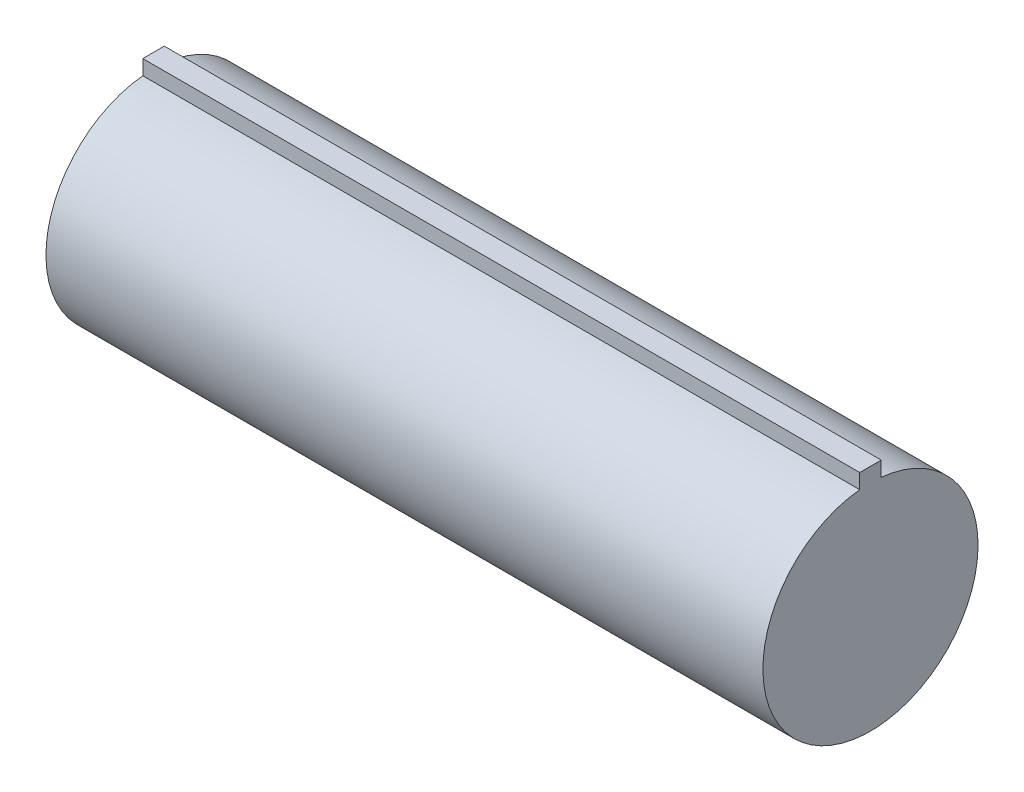
SolidWorks part; units mm, degrees
ref_plane "前视基准面" through (0, 0, 0) normal (0, 0, 1) x (1, 0, 0)
ref_plane "上视基准面" through (0, 0, 0) normal (0, 1, 0) x (1, 0, 0)
ref_plane "右视基准面" through (0, 0, 0) normal (1, 0, 0) x (0, 0, -1)
other "Configuration Table"
sketch "草图1" plane through (0, 0, 0) normal (1, 0, 0) x (0, 0, -1)
  line L1 (-1.5, 0) -> (1.5, 0)
  line L2 (-1.5, 0) -> (-1.5, 17)
  line L3 (-1.5, 17) -> (1.5, 17)
  line L4 (1.5, 0) -> (1.5, 17)
  circle A0 centre (0, 0) radius 15
  point P7 (0, 0)
  dimension "D1" = 30
  dimension "D2" = 3
  dimension "D3" = 17
extrude "凸台-拉伸1" add sketch "草图1" along normal blind 100 from offset 0 contours L2 A0 L4 L1 | A0 L4 L3 L2 | L4 A0 L2 L1
sketch "草图2" plane through (0, 0, 0) normal (-1, 0, 0) x (0, 0, 1)
  line L1 (-3, -3) -> (3, -3)
  line L2 (-3, -3) -> (-3, 3)
  line L3 (-3, 3) -> (3, 3)
  line L4 (3, -3) -> (3, 3)
  line L5 (-3, -3) -> (3, 3) construction
  line L6 (-3, 3) -> (3, -3) construction
  point P0 (0, 0)
  dimension "D1" = 6
  dimension "D2" = 6
extrude "切除-拉伸1" cut sketch "草图2" against normal blind 15
